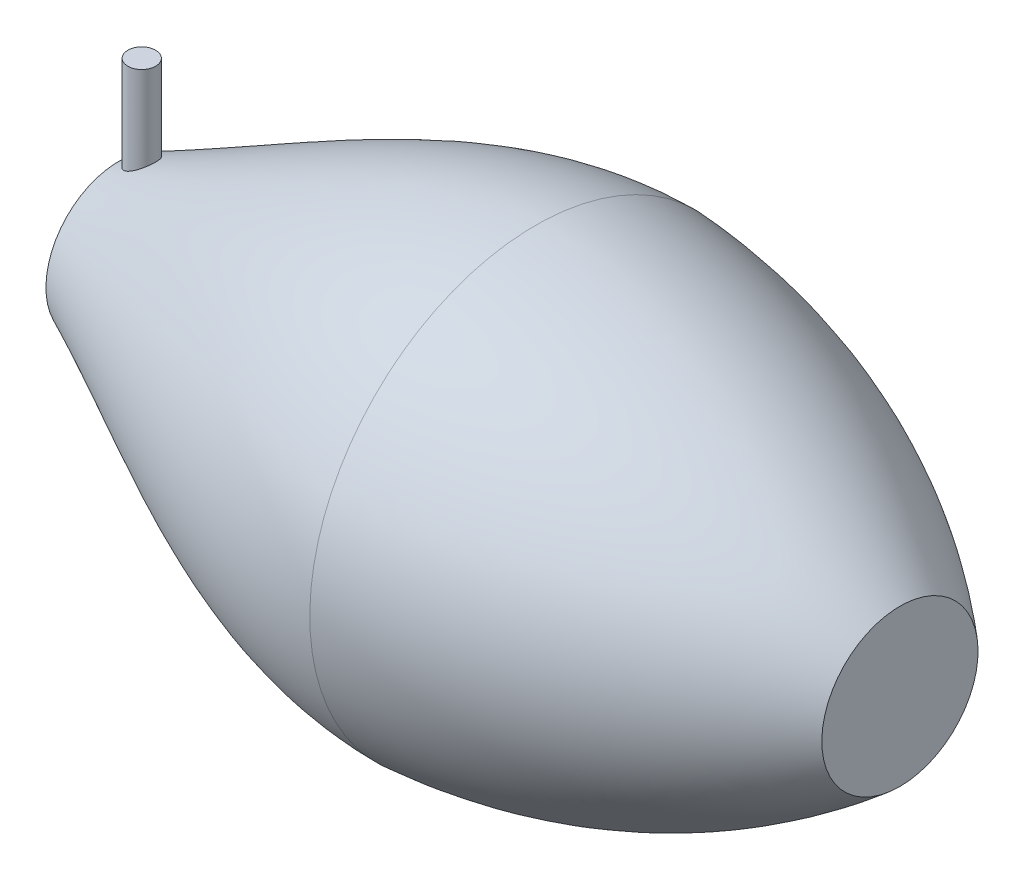
SolidWorks part; units mm, degrees
ref_plane "Front Plane" through (0, 0, 0) normal (0, 0, 1) x (1, 0, 0)
ref_plane "Top Plane" through (0, 0, 0) normal (0, 1, 0) x (1, 0, 0)
ref_plane "Right Plane" through (0, 0, 0) normal (1, 0, 0) x (0, 0, -1)
sketch "Sketch1" plane through (0, 0, 0) normal (0, 0, 1) x (1, 0, 0)
  line L0 (0, 65) -> (115.8629, 65) construction
  line L1 (0, 65) -> (0, 0) construction
  line L2 (0, 0) -> (120, 0) construction
  line L3 (105, 22.5) -> (105, 0)
  line L4 (0, 0) -> (-120, 0) construction
  line L5 (-120, 21) -> (-120, 0) construction
  line L6 (-120, 21) -> (-120, 0)
  line L7 (-120, 0) -> (105, 0)
  spline S0 degree 2 poles (0, 65) (59.0932, 61.0778) (105, 22.5) knots 0 0 0 1 1 1
  spline S1 degree 3 poles (-120, 21) (-81.3166, 38.8635) (-44.6367, 64.5752) (0, 65) knots 0 0 0 0 1 1 1 1
  point P0 (0, 65)
  point P3 (49, 55)
  point P6 (105, 22.5)
  point P7 (120, 15.7864)
  point P8 (-49, 55)
  point P11 (-88, 37)
  point P14 (-120, 21)
  dimension "D3" = 120
  dimension "D1" = 65
  dimension "D2" = 49
  dimension "D4" = 55
  dimension "D5" = 105
  dimension "D6" = 22.5
  dimension "D7" = 88
  dimension "D8" = 37
  dimension "D9" = 120
  dimension "D10" = 21
revolve "Revolve1" add sketch "Sketch1" angle 360 about L7
sketch "Sketch2" plane through (0, 0, 0) normal (0, 1, 0) x (1, 0, 0)
  circle A0 centre (-113.4107, 0) radius 4
  dimension "D1" = 8
extrude "Boss-Extrude1" add sketch "Sketch2" along normal blind 50
